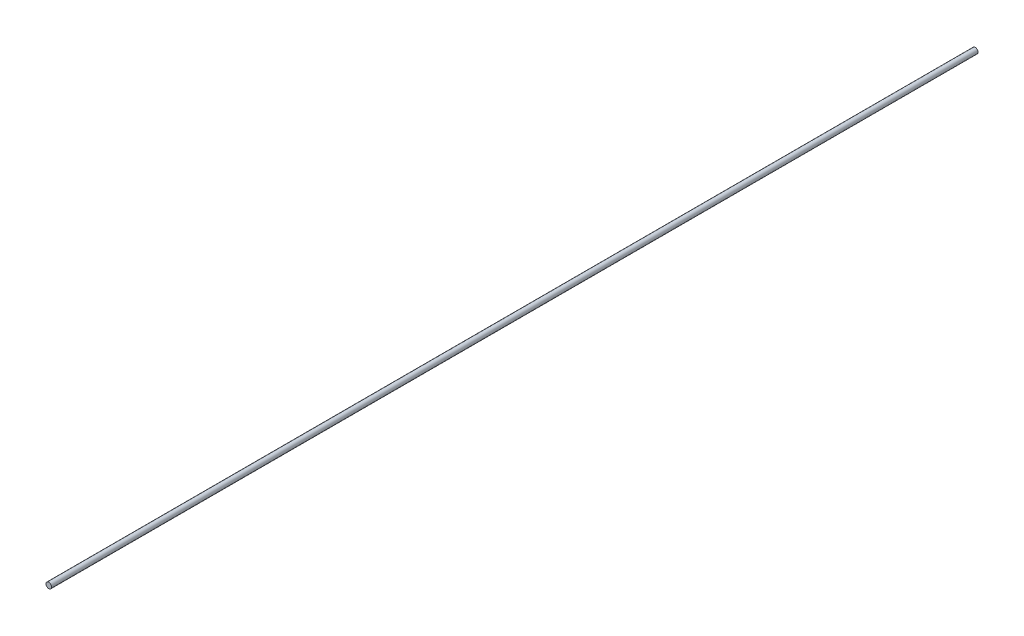
SolidWorks part; units mm, degrees
ref_plane "Front Plane" through (0, 0, 0) normal (0, 0, 1) x (1, 0, 0)
ref_plane "Top Plane" through (0, 0, 0) normal (0, 1, 0) x (1, 0, 0)
ref_plane "Right Plane" through (0, 0, 0) normal (1, 0, 0) x (0, 0, -1)
sketch "Sketch1" plane through (0, 0, 0) normal (0, 0, 1) x (1, 0, 0)
  circle A0 centre (0, 0) radius 0.9
  dimension "D1" = 1.8
extrude "Boss-Extrude1" add sketch "Sketch1" along normal blind 300
